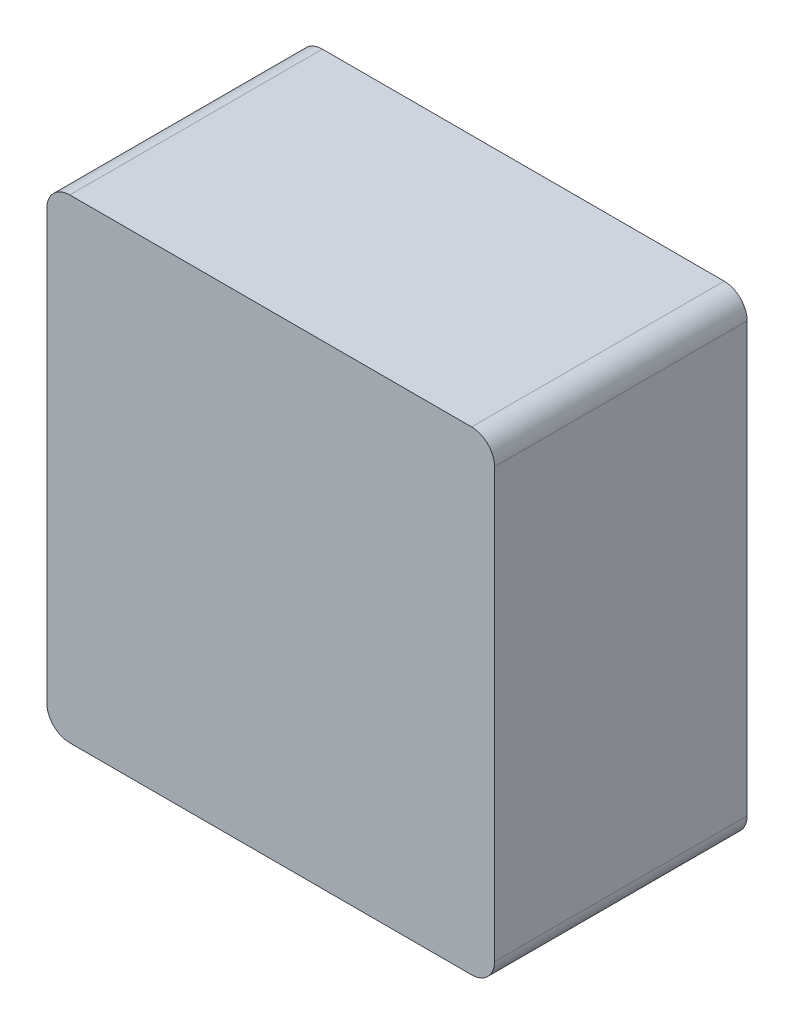
SolidWorks part; units mm, degrees
ref_plane "Спереди" through (0, 0, 0) normal (0, 0, 1) x (1, 0, 0)
ref_plane "Сверху" through (0, 0, 0) normal (0, 1, 0) x (1, 0, 0)
ref_plane "Справа" through (0, 0, 0) normal (1, 0, 0) x (0, 0, -1)
sketch "Эскиз1" plane through (0, 0, -7) normal (0, 0, 1) x (1, 0, 0)
  line L4 (-26.25, -31) -> (26.25, -31)
  line L5 (29.25, -28) -> (29.25, 28)
  line L6 (26.25, 31) -> (-26.25, 31)
  line L7 (-29.25, 28) -> (-29.25, -28)
  line L20 (-27.15, 28.9) -> (-27.15, -28.9)
  line L21 (27.15, 28.9) -> (-27.15, 28.9)
  line L22 (-27.15, -28.9) -> (27.15, -28.9)
  line L23 (27.15, -28.9) -> (27.15, 28.9)
  arc A4 (26.25, -31) -> (29.25, -28) centre (26.25, -28) ccw
  arc A5 (29.25, 28) -> (26.25, 31) centre (26.25, 28) ccw
  arc A6 (-26.25, 31) -> (-29.25, 28) centre (-26.25, 28) ccw
  arc A7 (-29.25, -28) -> (-26.25, -31) centre (-26.25, -28) ccw
extrude "Бобышка-Вытянуть1" add sketch "Эскиз1" along normal blind 30
sketch "Эскиз2" plane through (0, 0, 23) normal (0, 0, 1) x (1, 0, 0)
  line L0 (-26.25, -31) -> (26.25, -31) construction
  line L1 (-29.25, 28) -> (-29.25, -28) construction
  line L2 (26.25, 31) -> (-26.25, 31) construction
  line L3 (29.25, -28) -> (29.25, 28) construction
  line L4 (-26.25, -31) -> (26.25, -31)
  line L5 (-29.25, 28) -> (-29.25, -28)
  line L6 (26.25, 31) -> (-26.25, 31)
  line L7 (29.25, -28) -> (29.25, 28)
  arc A0 (26.25, -31) -> (29.25, -28) centre (26.25, -28) ccw construction
  arc A1 (-29.25, -28) -> (-26.25, -31) centre (-26.25, -28) ccw construction
  arc A2 (-26.25, 31) -> (-29.25, 28) centre (-26.25, 28) ccw construction
  arc A3 (29.25, 28) -> (26.25, 31) centre (26.25, 28) ccw construction
  arc A4 (26.25, -31) -> (29.25, -28) centre (26.25, -28) ccw
  arc A5 (-29.25, -28) -> (-26.25, -31) centre (-26.25, -28) ccw
  arc A6 (-26.25, 31) -> (-29.25, 28) centre (-26.25, 28) ccw
  arc A7 (29.25, 28) -> (26.25, 31) centre (26.25, 28) ccw
extrude "Бобышка-Вытянуть2" add sketch "Эскиз2" along normal blind 3
fillet "Скругление1" radius 2.5 4 edges at (0, -28.9, 23) (27.15, 0, 23) (0, 28.9, 23) (-27.15, 0, 23)
